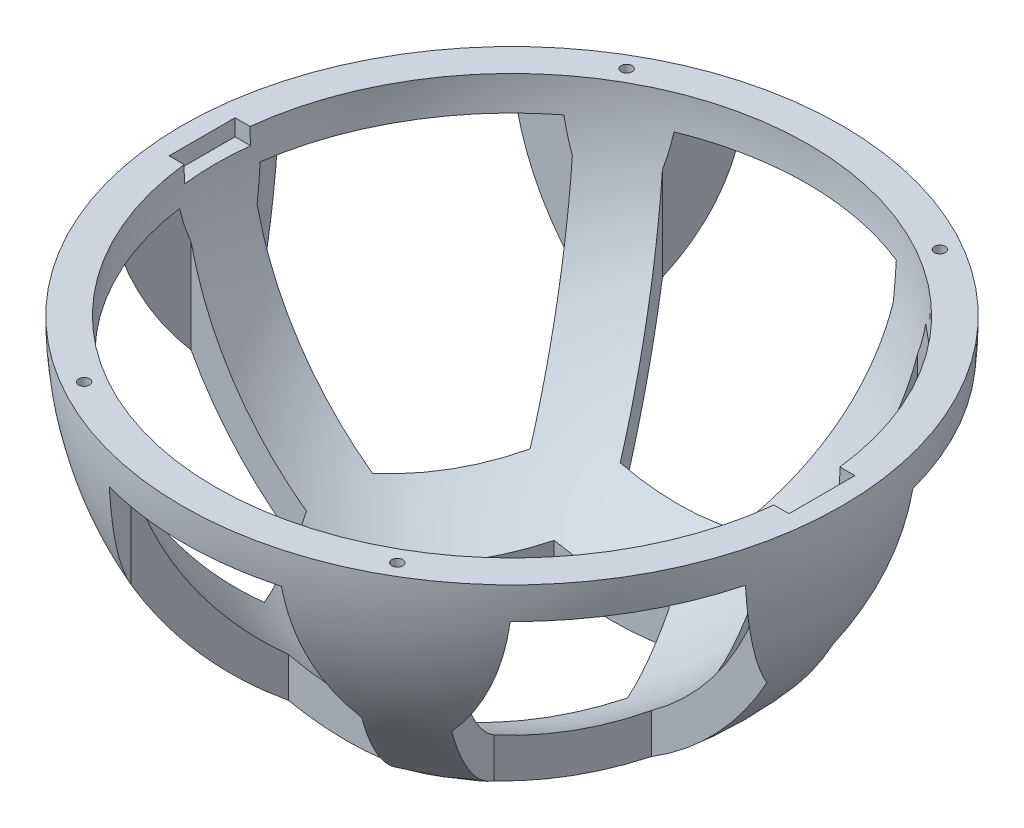
SolidWorks part; units mm, degrees
material "PLA"
ref_plane "Alzado" through (0, 0, 0) normal (0, 0, 1) x (1, 0, 0)
ref_plane "Planta" through (0, 0, 0) normal (0, 1, 0) x (1, 0, 0)
ref_plane "Vista lateral" through (0, 0, 0) normal (1, 0, 0) x (0, 0, -1)
sketch "Croquis1" plane through (0, 0, 0) normal (0, 1, 0) x (1, 0, 0)
  line L0 (0, -100) -> (0, 100) construction
  line L1 (0, 100) -> (0, -100) construction
  arc A0 (0, 100) -> (0, -100) centre (0, 0) cw
  point P4 (0, 0)
  dimension "D1" = 200
revolve "Revolución-Lámina1" add sketch "Croquis1" angle 180 about L1
sketch "Croquis2" plane through (0, 0, 0) normal (0, 1, 0) x (1, 0, 0)
  line L0 (0, 0) -> (0, 80.6218) construction
  line L79 (17.5, 30.3109) -> (-17.5, 30.3109)
  line L80 (-17.5, 30.3109) -> (-35, 0)
  line L81 (-35, 0) -> (-17.5, -30.3109)
  line L82 (-17.5, -30.3109) -> (17.5, -30.3109)
  line L83 (17.5, -30.3109) -> (35, 0)
  line L84 (35, 0) -> (17.5, 30.3109)
  line L85 (104.8205, 40.3109) -> (87.3205, 70.6218)
  line L86 (17.5, 110.9327) -> (-17.5, 110.9327)
  line L87 (-17.5, 110.9327) -> (-35, 80.6218)
  line L88 (-35, 80.6218) -> (-17.5, 50.3109)
  line L89 (-17.5, 50.3109) -> (17.5, 50.3109)
  line L90 (17.5, 50.3109) -> (35, 80.6218)
  line L91 (35, 80.6218) -> (17.5, 110.9327)
  line L92 (87.3205, 70.6218) -> (52.3205, 70.6218)
  line L93 (52.3205, 70.6218) -> (34.8205, 40.3109)
  line L94 (34.8205, 40.3109) -> (52.3205, 10)
  line L95 (52.3205, 10) -> (87.3205, 10)
  line L96 (87.3205, 10) -> (104.8205, 40.3109)
  line L97 (87.3205, -70.6218) -> (104.8205, -40.3109)
  line L98 (104.8205, -40.3109) -> (87.3205, -10)
  line L99 (87.3205, -10) -> (52.3205, -10)
  line L100 (52.3205, -10) -> (34.8205, -40.3109)
  line L101 (34.8205, -40.3109) -> (52.3205, -70.6218)
  line L102 (52.3205, -70.6218) -> (87.3205, -70.6218)
  line L103 (-17.5, -110.9327) -> (17.5, -110.9327)
  line L104 (17.5, -110.9327) -> (35, -80.6218)
  line L105 (35, -80.6218) -> (17.5, -50.3109)
  line L106 (17.5, -50.3109) -> (-17.5, -50.3109)
  line L107 (-17.5, -50.3109) -> (-35, -80.6218)
  line L108 (-35, -80.6218) -> (-17.5, -110.9327)
  line L109 (-104.8205, -40.3109) -> (-87.3205, -70.6218)
  line L110 (-87.3205, -70.6218) -> (-52.3205, -70.6218)
  line L111 (-52.3205, -70.6218) -> (-34.8205, -40.3109)
  line L112 (-34.8205, -40.3109) -> (-52.3205, -10)
  line L113 (-52.3205, -10) -> (-87.3205, -10)
  line L114 (-87.3205, -10) -> (-104.8205, -40.3109)
  line L115 (-87.3205, 70.6218) -> (-104.8205, 40.3109)
  line L116 (-104.8205, 40.3109) -> (-87.3205, 10)
  line L117 (-87.3205, 10) -> (-52.3205, 10)
  line L118 (-52.3205, 10) -> (-34.8205, 40.3109)
  line L119 (-34.8205, 40.3109) -> (-52.3205, 70.6218)
  line L120 (-52.3205, 70.6218) -> (-87.3205, 70.6218)
  circle A0 centre (0, 0) radius 30.3109 construction
  circle A1 centre (0, 80.6218) radius 30.3109 construction
  point P51 (0, 0)
  point P55 (0, 0)
  dimension "D1" = 35
  dimension "D2" = 6
  dimension "D3" = 35
  dimension "1.5" = 20
extrude "Cortar-Extruir1" cut sketch "Croquis2" against normal blind 100 from offset 10 offset against normal yes
ref_plane "Plano1" through (90, 0, 0) normal (-1, 0, 0) x (0, 0, 1)
sketch "Croquis4" plane through (90, 0, 0) normal (-1, 0, 0) x (0, 0, 1)
  line L1 (10, 5) -> (-10, 5)
  line L2 (10, 5) -> (10, -5)
  line L3 (10, -5) -> (-10, -5)
  line L4 (-10, 5) -> (-10, -5)
  line L5 (10, 5) -> (-10, -5) construction
  line L6 (10, -5) -> (-10, 5) construction
  point P0 (0, 0)
  dimension "D1" = 20
  dimension "D2" = 10
extrude "Cortar-Extruir2" cut sketch "Croquis4" against normal blind 4 and the other way blind 184
sketch "Croquis5" plane through (0, 0, 0) normal (0, 1, 0) x (1, 0, 0)
  line L0 (0, 0) -> (47.5, 82.2724) construction
  line L1 (-13.1089, 0) -> (14.5035, 0) construction
  line L2 (0, -14.9219) -> (0, 14.9219) construction
  line L3 (0, 0) -> (47.5, -82.2724) construction
  line L4 (0, 0) -> (-47.5, -82.2724) construction
  line L5 (0, 0) -> (-47.5, 82.2724) construction
  point P1 (47.5, 82.2724)
  point P7 (47.5, -82.2724)
  point P8 (-47.5, -82.2724)
  point P9 (-47.5, 82.2724)
  point P12 (-47.5, 82.2724)
  point P16 (47.5, 82.2724)
  point P20 (47.5, -82.2724)
  point P24 (-47.5, -82.2724)
  point P26 (-47.5, -82.2724)
  dimension "D1" = 30
  dimension "D2" = 95
hole_wizard "Taladro roscado M4x0.71" positions "Croquis5" profile "Croquis6" tap size "M4x0.7" standard "Ansi Metric"
sketch "Croquis6" plane through (-47.5, 0, 82.2724) normal (1, 0, 0) x (0, 0, 1)
  line L0 (0, 0) -> (0, 12.9914)
  line L1 (0, 12.9914) -> (1.65, 12)
  line L2 (1.65, 12) -> (1.65, 0)
  line L5 (1.65, 0) -> (0, 0)
  line L10 (0, 12.9914) -> (-1.65, 12) construction
  line L11 (0, -6.35) -> (0, 107.95) construction
  dimension "Diámetro de perforador para roscar" = 3.3
  dimension "Profundidad de perforador para roscar" = 12
  dimension "Ángulo de perforador" = 118
cosmetic thread "Rosca de taladro2" parameters "D1"=8, "D2"=4
cosmetic thread "Rosca de taladro3" parameters "D1"=8, "D2"=4
cosmetic thread "Rosca de taladro4" parameters "D1"=8, "D2"=4
cosmetic thread "Rosca de taladro5" parameters "D1"=8, "D2"=4
cosmetic thread "Rosca de taladro6" parameters "D1"=8, "D2"=4
